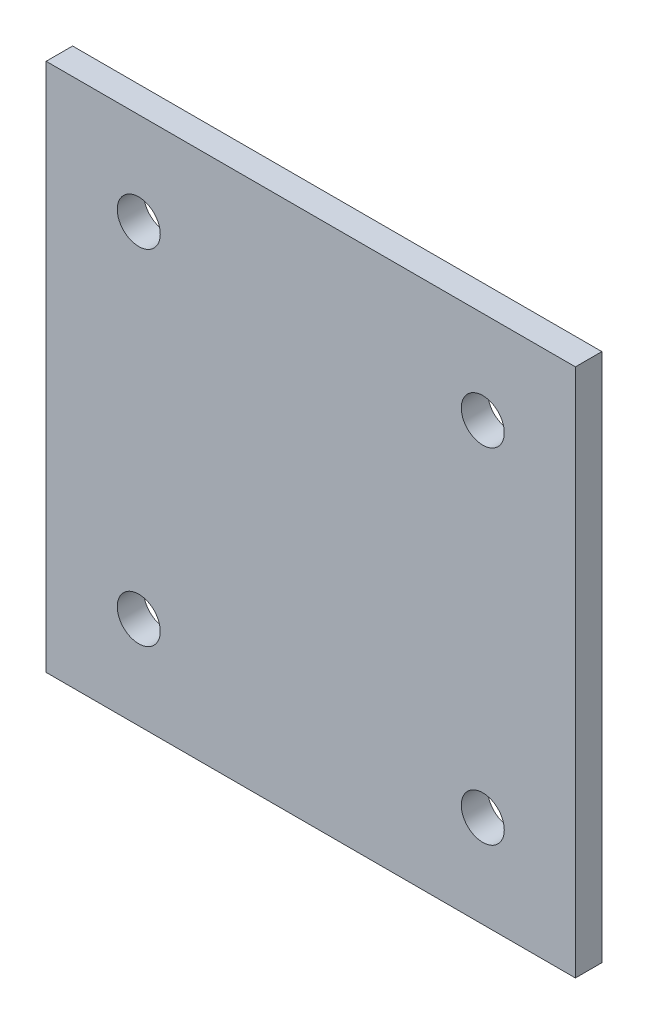
SolidWorks part; units mm, degrees
ref_plane "Front Plane" through (0, 0, 0) normal (0, 0, 1) x (1, 0, 0)
ref_plane "Top Plane" through (0, 0, 0) normal (0, 1, 0) x (1, 0, 0)
ref_plane "Right Plane" through (0, 0, 0) normal (1, 0, 0) x (0, 0, -1)
sketch "Sketch2" plane through (0, 0, 0) normal (0, 0, 1) x (1, 0, 0)
  line L0 (-20, 0) -> (0, 0) construction
  line L1 (-20, -20) -> (20, -20)
  line L2 (-20, -20) -> (-20, 20)
  line L3 (-20, 20) -> (20, 20)
  line L4 (20, -20) -> (20, 20)
  line L5 (-20, -20) -> (20, 20) construction
  line L6 (-20, 20) -> (20, -20) construction
  line L7 (0, 0) -> (0, 20) construction
  circle A0 centre (-13, 13) radius 1.625
  circle A1 centre (-13, -13) radius 1.625
  circle A2 centre (13, -13) radius 1.625
  circle A3 centre (13, 13) radius 1.625
  point P0 (0, 0)
  dimension "D2" = 3.25
  dimension "D1" = 40
  dimension "D3" = 13
extrude "Boss-Extrude1" add sketch "Sketch2" along normal blind 2
